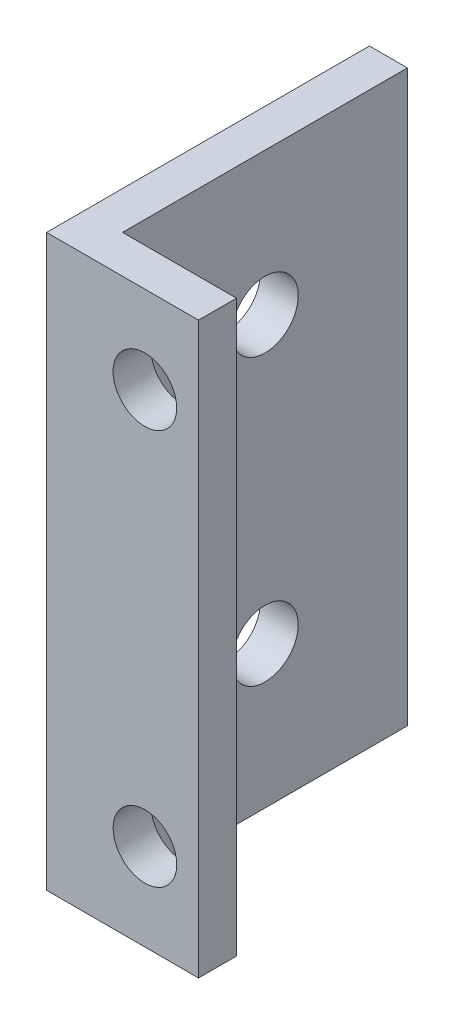
SolidWorks part; units mm, degrees
ref_plane "Front Plane" through (0, 0, 0) normal (0, 0, 1) x (1, 0, 0)
ref_plane "Top Plane" through (0, 0, 0) normal (0, 1, 0) x (1, 0, 0)
ref_plane "Right Plane" through (0, 0, 0) normal (1, 0, 0) x (0, 0, -1)
sketch "Sketch1" plane through (0, 0, 0) normal (0, 1, 0) x (1, 0, 0)
  line L0 (-2.5361, 10.7397) -> (-2.5361, -4.2603)
  line L1 (-4.5361, 10.7397) -> (-2.5361, 10.7397)
  line L2 (-4.5361, 10.7397) -> (-4.5361, -6.2603)
  line L3 (-4.5361, -6.2603) -> (3.4639, -6.2603)
  line L4 (3.4639, -4.2603) -> (3.4639, -6.2603)
  line L7 (-2.5361, -4.2603) -> (3.4639, -4.2603)
  point P0 (0.0704, -0.0352)
  dimension "D1" = 2
  dimension "D2" = 2
  dimension "D3" = 15
  dimension "D4" = 6
extrude "Boss-Extrude1" add sketch "Sketch1" along normal blind 30
sketch "Sketch2" plane through (0, 0, 4.2603) normal (0, 0, -1) x (-1, 0, 0)
  line L0 (2.5361, 30) -> (2.5361, 0) construction
  line L1 (2.5361, 30) -> (2.5361, 0) construction
  line L2 (-3.4639, 15) -> (9.7039, 15) construction
  line L3 (-3.4639, 30) -> (-3.4639, 0) construction
  circle A0 centre (-0.6389, 25.414) radius 1.675
  circle A1 centre (-0.6439, 4.59) radius 1.675
  dimension "D1" = 3.175
  dimension "D2" = 3.35
  dimension "D4" = 3.35
  dimension "D3" = 3.18
  dimension "D5" = 10.414
  dimension "D6" = 10.41
extrude "Cut-Extrude1" cut sketch "Sketch2" against normal blind 30
sketch "Sketch3" plane through (-2.5361, 0, 0) normal (1, 0, 0) x (0, 0, -1)
  line L0 (-4.2603, 30) -> (-4.2603, 0) construction
  line L3 (-4.2603, 30) -> (10.7397, 30) construction
  line L4 (-4.2603, 0) -> (10.7397, 0) construction
  circle A0 centre (3.2397, 22.5) radius 1.75
  circle A1 centre (3.2397, 7.5) radius 1.75
  dimension "D1" = 3.5
  dimension "D2" = 3.5
  dimension "D3" = 7.5
  dimension "D4" = 7.5
  dimension "D5" = 7.5
  dimension "D6" = 7.5
extrude "Cut-Extrude2" cut sketch "Sketch3" against normal blind 30
